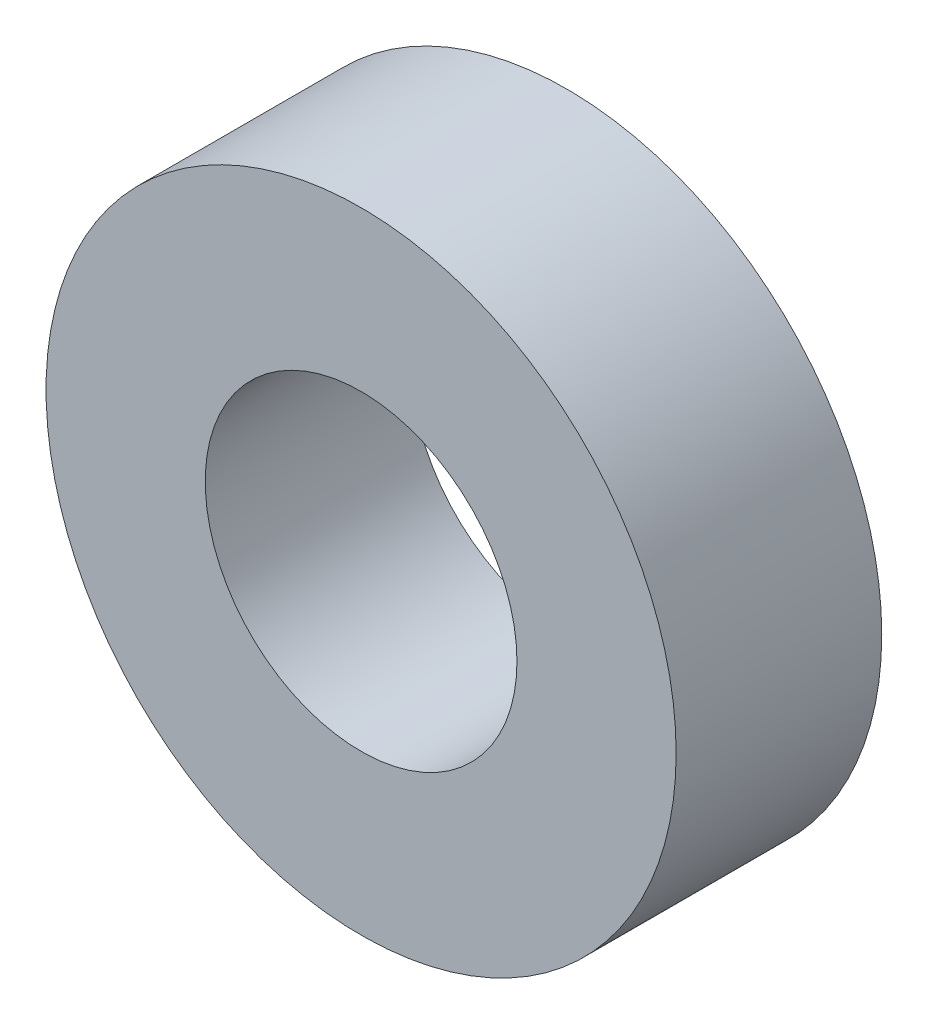
SolidWorks part; units mm, degrees
other "Defeature"
material "Nylon"
ref_plane "Front Plane" through (0, 0, 0) normal (0, 0, 1) x (1, 0, 0)
ref_plane "Top Plane" through (0, 0, 0) normal (0, 1, 0) x (1, 0, 0)
ref_plane "Right Plane" through (0, 0, 0) normal (1, 0, 0) x (0, 0, -1)
sketch "Sketch1" plane through (0, 0, 0) normal (0, 0, 1) x (1, 0, 0)
  circle A0 centre (0, 0) radius 4.75
  dimension "D1" = 9.5
extrude "Boss-Extrude1" add sketch "Sketch1" against normal mid plane 3.1
sketch "Sketch2" plane through (0, 0, 1.55) normal (0, 0, 1) x (1, 0, 0)
  circle A0 centre (0, 0) radius 2.35
  dimension "D1" = 4.7
extrude "Cut-Extrude1" cut sketch "Sketch2" against normal through all
